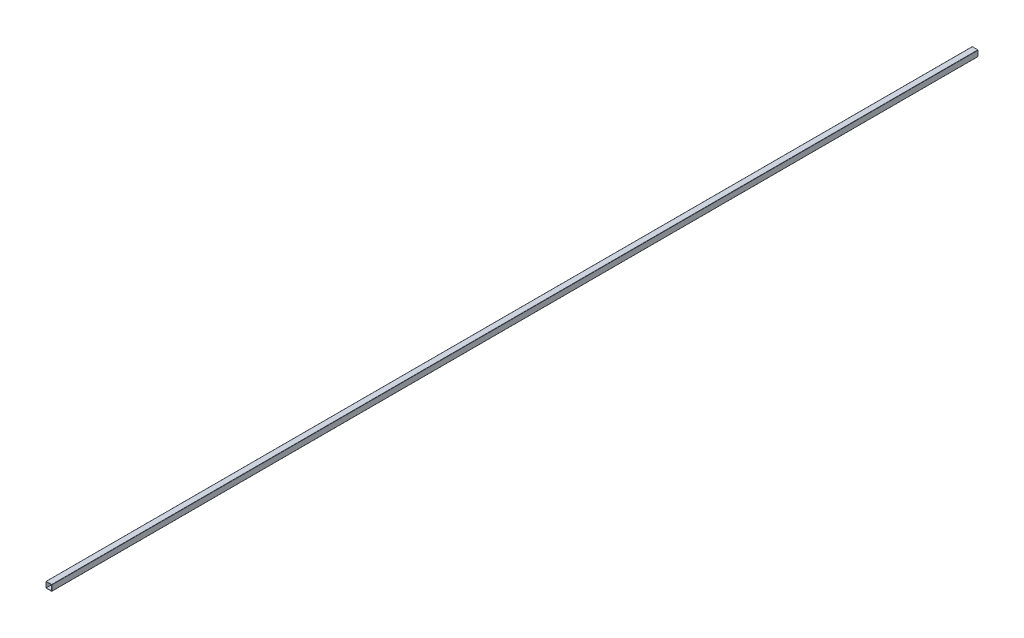
SolidWorks part; units mm, degrees
ref_plane "Alzado" through (0, 0, 0) normal (0, 0, 1) x (1, 0, 0)
ref_plane "Planta" through (0, 0, 0) normal (0, 1, 0) x (1, 0, 0)
ref_plane "Vista lateral" through (0, 0, 0) normal (1, 0, 0) x (0, 0, -1)
sketch "Croquis1" plane through (0, 0, 0) normal (0, 0, 1) x (1, 0, 0)
  line L0 (-17.55, -17.55) -> (-17.55, 17.55)
  line L1 (-17.55, -19.05) -> (17.55, -19.05)
  line L2 (-19.05, -17.55) -> (-19.05, 17.55)
  line L3 (-17.55, 19.05) -> (17.55, 19.05)
  line L4 (19.05, -17.55) -> (19.05, 17.55)
  line L5 (-19.05, -19.05) -> (19.05, 19.05) construction
  line L6 (-19.05, 19.05) -> (19.05, -19.05) construction
  line L7 (-17.55, 17.55) -> (17.55, 17.55)
  line L8 (17.55, -17.55) -> (17.55, 17.55)
  line L9 (-17.55, -17.55) -> (17.55, -17.55)
  arc A0 (17.55, 19.05) -> (19.05, 17.55) centre (17.55, 17.55) cw
  arc A1 (17.55, -19.05) -> (19.05, -17.55) centre (17.55, -17.55) ccw
  arc A2 (-17.55, -19.05) -> (-19.05, -17.55) centre (-17.55, -17.55) cw
  arc A3 (-19.05, 17.55) -> (-17.55, 19.05) centre (-17.55, 17.55) cw
  arc A4 (-17.55, 17.55) -> (-17.55, 17.55) centre (-17.55, 17.55) cw
  arc A5 (17.55, 17.55) -> (17.55, 17.55) centre (17.55, 17.55) cw
  arc A6 (17.55, -17.55) -> (17.55, -17.55) centre (17.55, -17.55) ccw
  arc A7 (-17.55, -17.55) -> (-17.55, -17.55) centre (-17.55, -17.55) cw
  point P0 (0, 0)
  dimension "D2" = 1.5
  dimension "D1" = 38.1
  dimension "D3" = 1.5
extrude "Saliente-Extruir1" add sketch "Croquis1" along normal blind 6000
